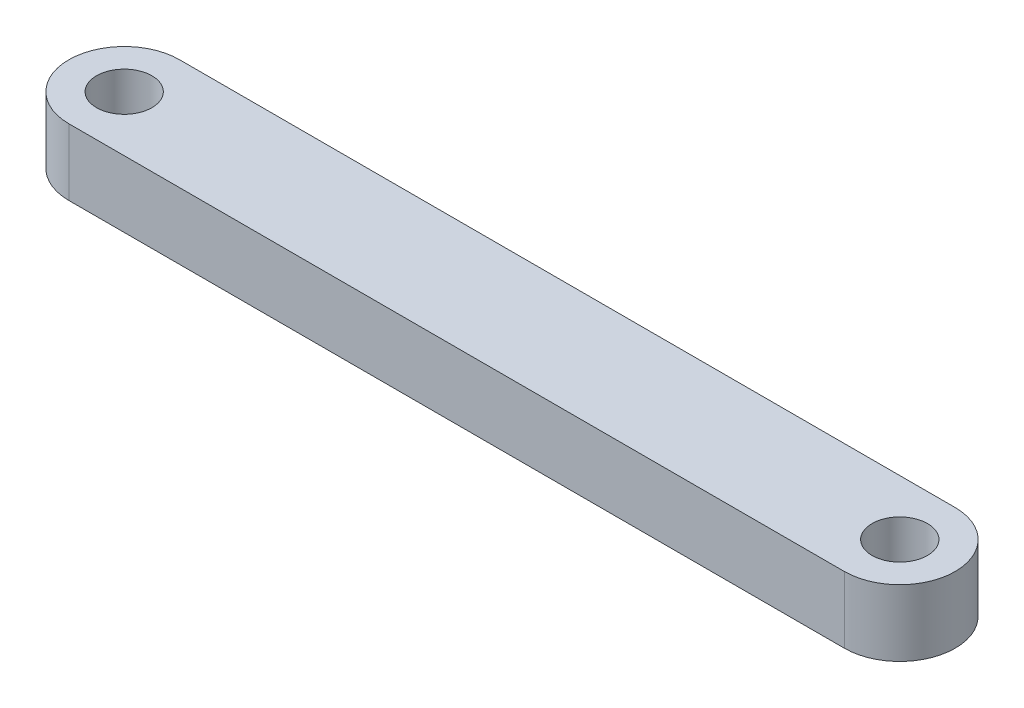
SolidWorks part; units mm, degrees
ref_plane "Front Plane" through (0, 0, 0) normal (0, 0, 1) x (1, 0, 0)
ref_plane "Top Plane" through (0, 0, 0) normal (0, 1, 0) x (1, 0, 0)
ref_plane "Right Plane" through (0, 0, 0) normal (1, 0, 0) x (0, 0, -1)
sketch "Sketch1" plane through (0, 0, 0) normal (0, 1, 0) x (1, 0, 0)
  line L0 (0, 0) -> (35, 0) construction
  line L1 (0, 2.5) -> (35, 2.5)
  line L2 (0, -2.5) -> (35, -2.5)
  arc A0 (0, 2.5) -> (0, -2.5) centre (0, 0) ccw
  arc A1 (35, -2.5) -> (35, 2.5) centre (35, 0) ccw
  circle A2 centre (0, 0) radius 1.25
  circle A3 centre (35, 0) radius 1.25
  point P3 (17.5, 0)
  dimension "D3" = 2.5
  dimension "D1" = 5
  dimension "D2" = 35
extrude "Boss-Extrude1" add sketch "Sketch1" along normal blind 3
